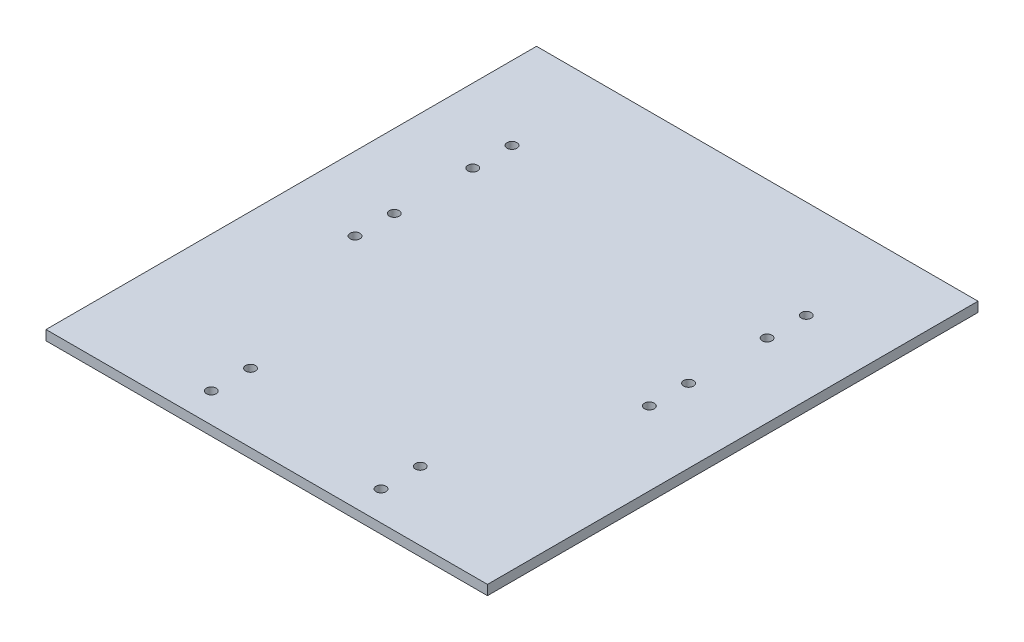
SolidWorks part; units mm, degrees
ref_plane "Front Plane" through (0, 0, 0) normal (0, 0, 1) x (1, 0, 0)
ref_plane "Top Plane" through (0, 0, 0) normal (0, 1, 0) x (1, 0, 0)
ref_plane "Right Plane" through (0, 0, 0) normal (1, 0, 0) x (0, 0, -1)
sketch "Sketch1" plane through (0, 0, 0) normal (0, 1, 0) x (1, 0, 0)
  line L1 (112.5, -125) -> (-112.5, -125)
  line L2 (112.5, -125) -> (112.5, 125)
  line L3 (112.5, 125) -> (-112.5, 125)
  line L4 (-112.5, -125) -> (-112.5, 125)
  line L5 (112.5, -125) -> (-112.5, 125) construction
  line L6 (112.5, 125) -> (-112.5, -125) construction
  point P0 (0, 0)
  dimension "D1" = 225
  dimension "D2" = 250
extrude "Body" add sketch "Sketch1" along normal blind 5
sketch "Sketch2" plane through (0, 5, 0) normal (0, 1, 0) x (1, 0, 0)
  line L0 (-1000, 35) -> (49000, 35) construction
  line L1 (0, -1000) -> (0, 49000) construction
  line L2 (-75, 75) -> (-75, 55) construction
  circle A0 centre (-75, 75) radius 2.5
  circle A1 centre (-75, 55) radius 2.5
  circle A2 centre (75, 55) radius 2.5
  circle A3 centre (75, 75) radius 2.5
  circle A4 centre (75, -5) radius 2.5
  circle A5 centre (75, 15) radius 2.5
  circle A6 centre (-75, -5) radius 2.5
  circle A7 centre (-75, 15) radius 2.5
  point P10 (-75, 65)
  dimension "D1" = 20
  dimension "D2" = 5
  dimension "D3" = 150
  dimension "D4" = 60
  dimension "D5" = 35
extrude "Fixation_Holes" cut sketch "Sketch2" against normal through all
sketch "Sketch3" plane through (0, 5, 0) normal (0, 1, 0) x (1, 0, 0)
  line L0 (0, -1000) -> (0, 49000) construction
  line L1 (-43.25, -90) -> (-43.25, -110) construction
  line L2 (-112.5, -125) -> (112.5, -125) construction
  circle A0 centre (-43.25, -90) radius 2.5
  circle A1 centre (-43.25, -110) radius 2.5
  circle A3 centre (43.25, -90) radius 2.5
  circle A4 centre (43.25, -110) radius 2.5
  point P5 (-43.25, -100)
  point P8 (-44.8283, -50)
  dimension "D2" = 20
  dimension "D3" = 5
  dimension "D1" = 86.5
  dimension "D4" = 25
extrude "Holes" cut sketch "Sketch3" against normal through all
